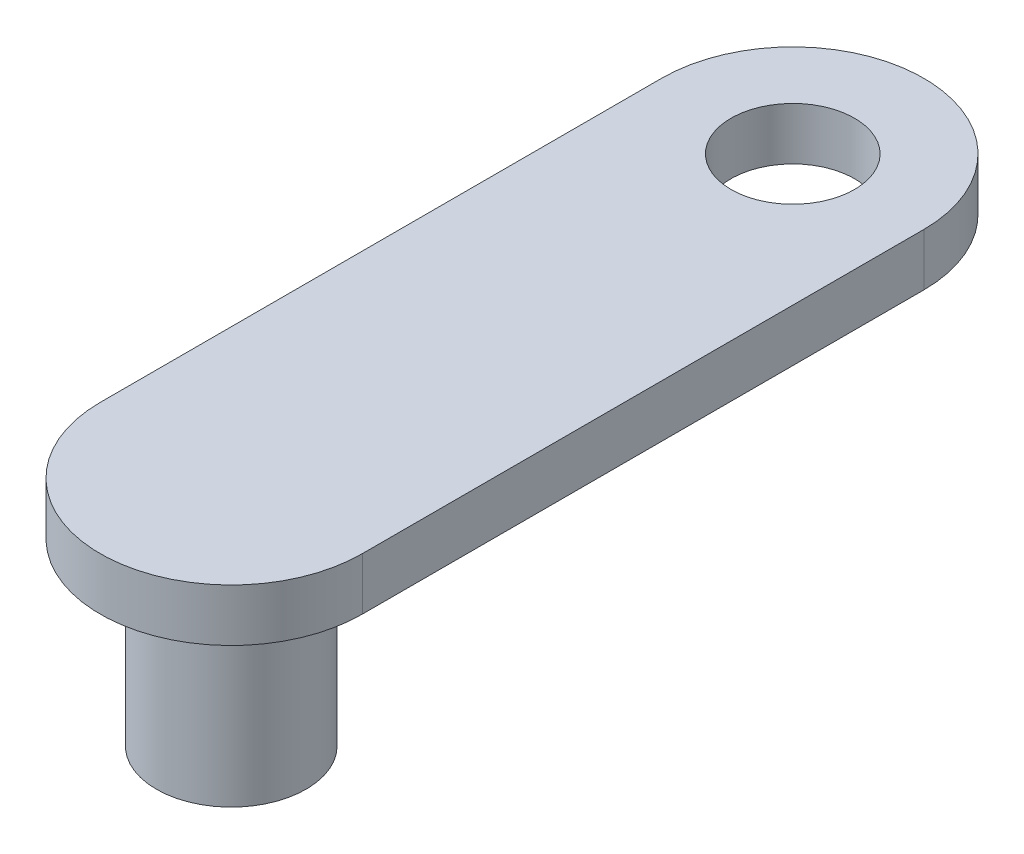
SolidWorks part; units mm, degrees
ref_plane "前视基准面" through (0, 0, 0) normal (0, 0, 1) x (1, 0, 0)
ref_plane "上视基准面" through (0, 0, 0) normal (0, 1, 0) x (1, 0, 0)
ref_plane "右视基准面" through (0, 0, 0) normal (1, 0, 0) x (0, 0, -1)
sketch "草图1" plane through (0, 0, 0) normal (0, 1, 0) x (1, 0, 0)
  circle A0 centre (0, 0) radius 2
  dimension "D1" = 4
extrude "凸台-拉伸1" add sketch "草图1" along normal blind 4.8
sketch "草图2" plane through (0, 4.8, 0) normal (0, 1, 0) x (1, 0, 0)
  line L5 (0, 0) -> (0, 15) construction
  line L6 (-3.5, 0) -> (-3.5, 15)
  line L7 (3.5, 0) -> (3.5, 15)
  circle A2 centre (0, 15) radius 1.65
  arc A3 (-3.5, 0) -> (3.5, 0) centre (0, 0) ccw
  arc A4 (3.5, 15) -> (-3.5, 15) centre (0, 15) ccw
  point P3 (0, 7.5)
  dimension "D1" = 3.3
  dimension "D3" = 3.5
  dimension "D2" = 15
extrude "凸台-拉伸2" add sketch "草图2" along normal blind 1.4
